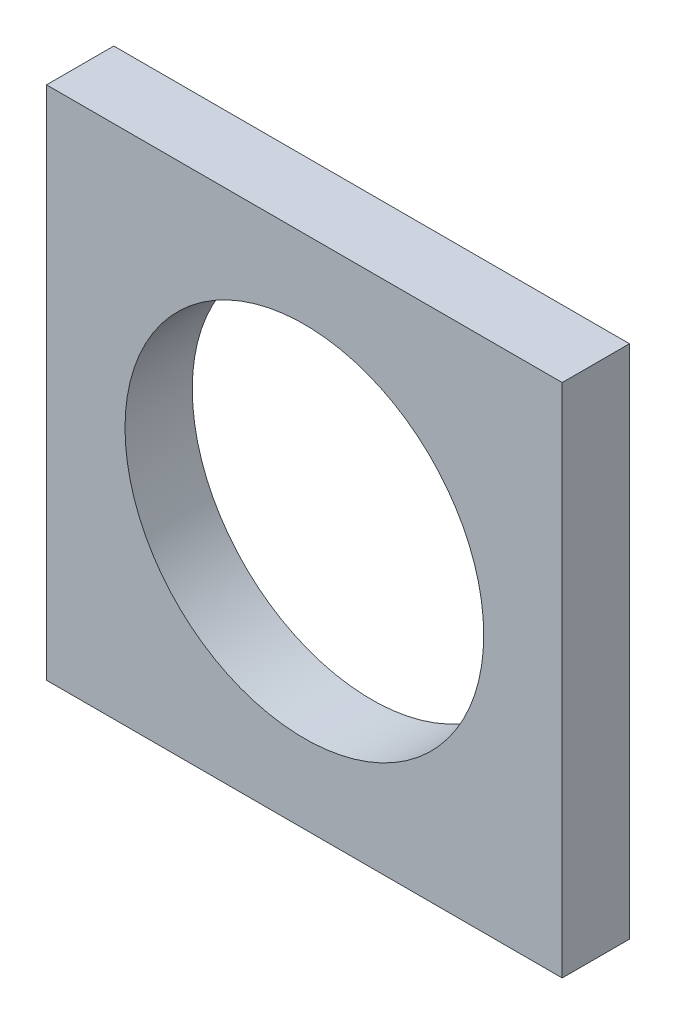
SolidWorks part; units mm, degrees
ref_plane "前视基准面" through (0, 0, 0) normal (0, 0, 1) x (1, 0, 0)
ref_plane "上视基准面" through (0, 0, 0) normal (0, 1, 0) x (1, 0, 0)
ref_plane "右视基准面" through (0, 0, 0) normal (1, 0, 0) x (0, 0, -1)
sketch "草图1" plane through (0, 0, 0) normal (0, 0, 1) x (1, 0, 0)
  line L1 (11.5, -11.5) -> (-11.5, -11.5)
  line L2 (11.5, -11.5) -> (11.5, 11.5)
  line L3 (11.5, 11.5) -> (-11.5, 11.5)
  line L4 (-11.5, -11.5) -> (-11.5, 11.5)
  line L5 (11.5, -11.5) -> (-11.5, 11.5) construction
  line L6 (11.5, 11.5) -> (-11.5, -11.5) construction
  circle A0 centre (0, 0) radius 8
  point P0 (0, 0)
extrude "凸台-拉伸1" add sketch "草图1" along normal blind 3
